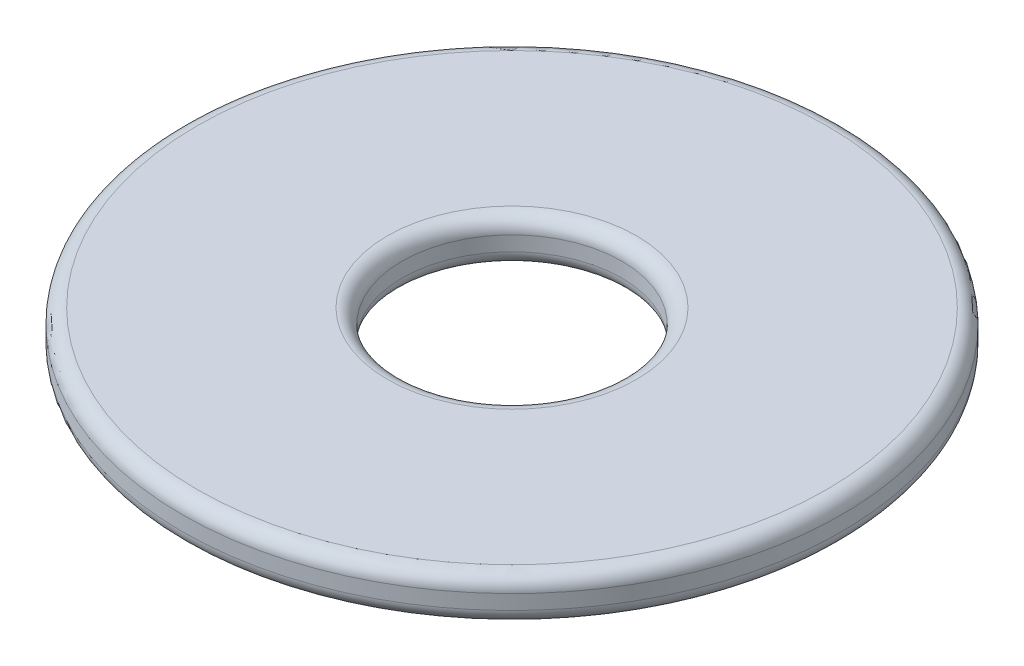
SolidWorks part; units mm, degrees
material "Cast Carbon Steel"
ref_plane "Front Plane" through (0, 0, 0) normal (0, 0, 1) x (1, 0, 0)
ref_plane "Top Plane" through (0, 0, 0) normal (0, 1, 0) x (1, 0, 0)
ref_plane "Right Plane" through (0, 0, 0) normal (1, 0, 0) x (0, 0, -1)
sketch "Sketch1" plane through (0, 0, 0) normal (0, 1, 0) x (1, 0, 0)
  circle A0 centre (0, 0) radius 9
  circle A1 centre (0, 0) radius 3
  dimension "D1" = 6
  dimension "D2" = 18
extrude "Boss-Extrude1" add sketch "Sketch1" along normal blind 1.2
fillet "Fillet1" radius 0.4 4 edges at (0, 0, 9) (0, 1.2, 9) (0, 0, 3) (0, 1.2, 3)
